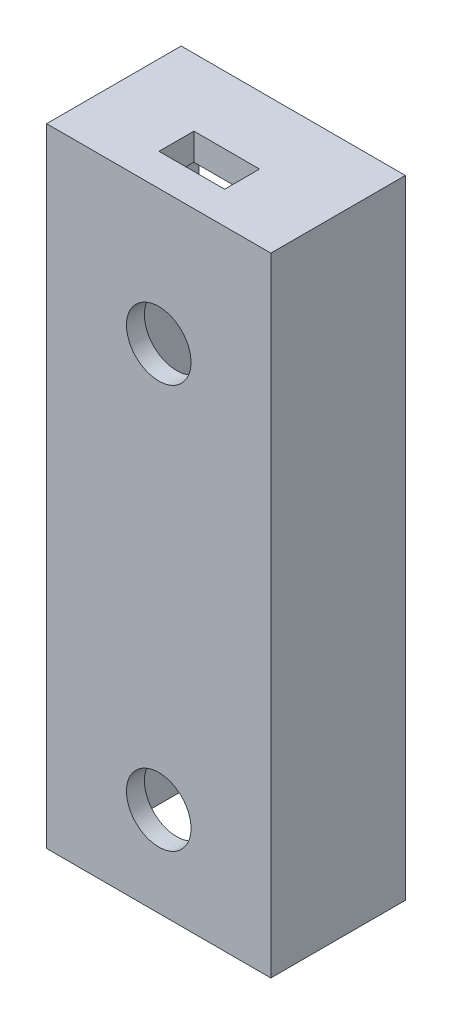
SolidWorks part; units mm, degrees
ref_plane "Front Plane" through (0, 0, 0) normal (0, 0, 1) x (1, 0, 0)
ref_plane "Top Plane" through (0, 0, 0) normal (0, 1, 0) x (1, 0, 0)
ref_plane "Right Plane" through (0, 0, 0) normal (1, 0, 0) x (0, 0, -1)
sketch "Sketch1" plane through (0, 0, 0) normal (0, 0, 1) x (1, 0, 0)
  line L0 (-12.5, -35) -> (12.5, -35)
  line L1 (-12.5, -35) -> (-12.5, 35)
  line L2 (12.5, -35) -> (12.5, 35)
  line L3 (-12.5, 35) -> (12.5, 35)
  line L4 (-12.5, -35) -> (12.5, 35) construction
  line L5 (12.5, -35) -> (-12.5, 35) construction
  point P1 (0, 0)
  dimension "D1" = 70
  dimension "D2" = 25
extrude "Boss-Extrude1" add sketch "Sketch1" against normal blind 15
sketch "Sketch2" plane through (0, 35, 0) normal (0, 1, 0) x (1, 0, 0)
  line L4 (12.5, 15) -> (-12.5, 15) construction
  line L5 (-10.5, 15) -> (10.5, 15)
  line L6 (-10.5, 15) -> (-10.5, 2)
  line L7 (-10.5, 2) -> (10.5, 2)
  line L8 (10.5, 15) -> (10.5, 2)
  line L9 (-12.5, 15) -> (-12.5, 0) construction
  line L10 (12.5, 15) -> (12.5, 0) construction
  line L11 (12.5, 0) -> (-12.5, 0) construction
  dimension "D1" = 2
  dimension "D2" = 2
  dimension "D3" = 2
extrude "Cut-Extrude1" cut sketch "Sketch2" against normal up to next
sketch "Sketch4" plane through (0, 35, 0) normal (0, 1, 0) x (1, 0, 0)
  line L1 (-12.5, 0) -> (12.5, 0)
  line L2 (-12.5, 0) -> (-12.5, 15)
  line L3 (-12.5, 15) -> (12.5, 15)
  line L4 (12.5, 0) -> (12.5, 15)
  line L5 (-3.5678, 3.5945) -> (3.7531, 3.5945)
  line L6 (-3.5678, 3.5945) -> (-3.5678, 7.4866)
  line L7 (-3.5678, 7.4866) -> (3.7531, 7.4866)
  line L8 (3.7531, 3.5945) -> (3.7531, 7.4866)
extrude "Boss-Extrude2" add sketch "Sketch4" against normal blind 3 contours L5 L8 L7 L6 | L2 L1 L4 L3
sketch "Sketch5" plane through (0, 0, -2) normal (0, 0, -1) x (-1, 0, 0)
  line L0 (-12.5, 35) -> (12.5, 35) construction
  line L1 (10.5, -35) -> (-10.5, -35) construction
  line L2 (-12.5, -35) -> (-12.5, 35) construction
  line L3 (12.5, 35) -> (12.5, -35) construction
  circle A0 centre (0, 20) radius 3.6
  circle A1 centre (0, -25) radius 3.6
  point P8 (0, -35)
  dimension "D1" = 7.2
  dimension "D2" = 12.5
  dimension "D6" = 7.2
  dimension "D3" = 15
  dimension "D4" = 10
  dimension "D5" = 12.5
extrude "Cut-Extrude3" cut sketch "Sketch5" against normal up to next
